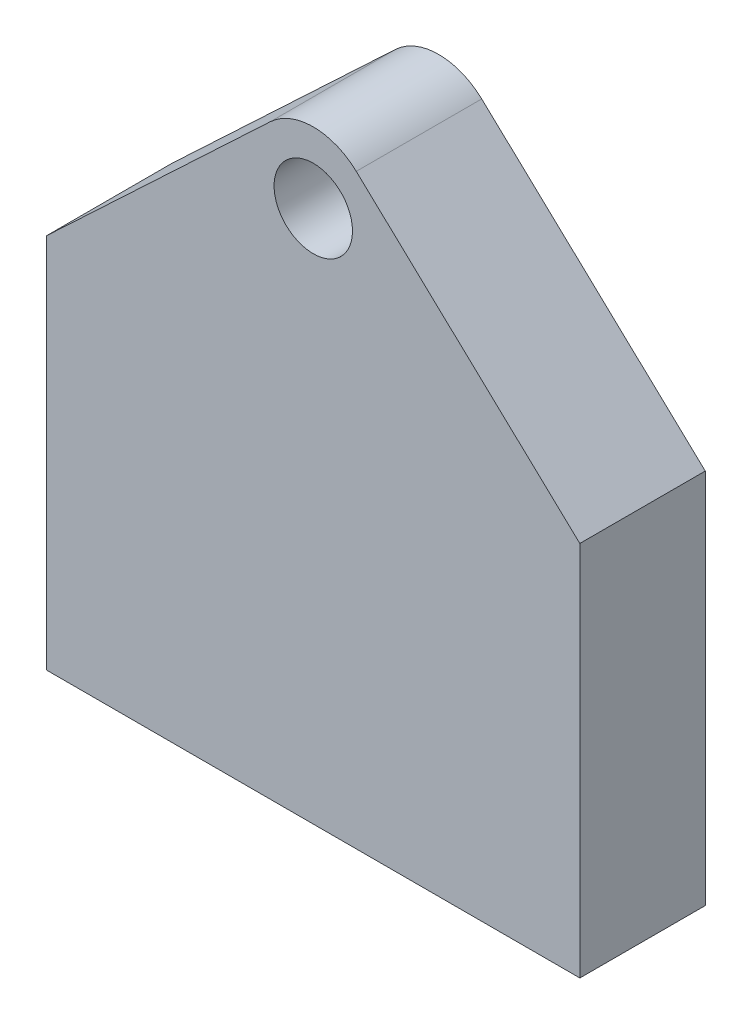
SolidWorks part; units mm, degrees
ref_plane "Front Plane" through (0, 0, 0) normal (0, 0, 1) x (1, 0, 0)
ref_plane "Top Plane" through (0, 0, 0) normal (0, 1, 0) x (1, 0, 0)
ref_plane "Right Plane" through (0, 0, 0) normal (1, 0, 0) x (0, 0, -1)
sketch "Sketch1" plane through (0, 0, 0) normal (0, 0, 1) x (1, 0, 0)
  line L0 (-53.975, 0) -> (53.975, 0)
  line L1 (55, 0) -> (-55, 0) construction
  line L2 (53.975, 0) -> (53.975, 76.2)
  line L3 (53.975, 76.2) -> (0, 127)
  line L4 (0, -55) -> (0, 55) construction
  line L5 (0, 127) -> (-53.975, 76.2)
  line L6 (-53.975, 76.2) -> (-53.975, 0)
  point P5 (-53.975, 38.1)
  dimension "D1" = 107.95
  dimension "D2" = 53.975
  dimension "D3" = 127
  dimension "D4" = 76.2
extrude "Boss-Extrude1" add sketch "Sketch1" along normal blind 25.4
fillet "Fillet1" radius 12.7 1 edges at (0, 127, 12.7)
sketch "Sketch2" plane through (0, 0, 25.4) normal (0, 0, 1) x (1, 0, 0)
  line L0 (13.97, 0) -> (-13.97, 0) construction
  circle A0 centre (0, 107.95) radius 7.9375
  dimension "D1" = 107.95
extrude "Cut-Extrude1" cut sketch "Sketch2" against normal blind 25.4
